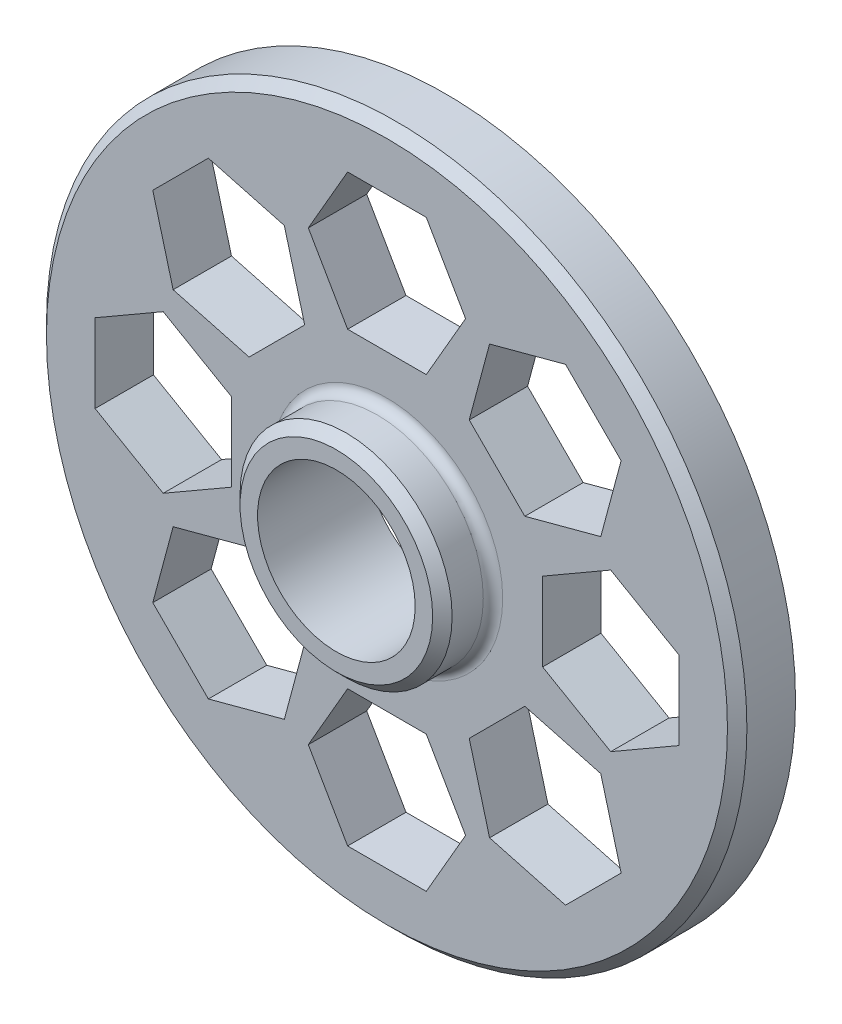
SolidWorks part; units mm, degrees
ref_plane "Alzado" through (0, 0, 0) normal (1, 0, 0) x (0, 1, 0)
ref_plane "Planta" through (0, 0, 0) normal (0, 0, 1) x (0, 1, 0)
ref_plane "Vista lateral" through (0, 0, 0) normal (0, 1, 0) x (-1, 0, 0)
sketch "Croquis1" plane through (0, 0, 0) normal (0, 0, 1) x (0, 1, 0)
  circle A0 centre (0, 0) radius 18
  dimension "D1" = 36
extrude "Saliente-Extruir1" add sketch "Croquis1" along normal blind 3
sketch "Croquis2" plane through (0, 0, 3) normal (0, 0, 1) x (1, 0, 0)
  circle A0 centre (0, 0) radius 5.45
  dimension "D1" = 10.9
extrude "Saliente-Extruir2" add sketch "Croquis2" along normal blind 2.6
chamfer "Chaflán1" distance 0.5 angle 45 2 edges at (18, 0, 3) (5.45, 0, 5.6)
fillet "Redondeo1" radius 0.5 1 edges at (5.45, 0, 3)
sketch "Croquis3" plane through (0, 0, 3) normal (0, 0, 1) x (1, 0, 0)
  line L0 (0, 0) -> (0, 18) construction
  line L2 (-4.0415, 11.5) -> (-2.0207, 8)
  line L3 (-2.0207, 8) -> (2.0207, 8)
  line L4 (2.0207, 8) -> (4.0415, 11.5)
  line L5 (4.0415, 11.5) -> (2.0207, 15)
  line L6 (2.0207, 15) -> (-2.0207, 15)
  line L7 (-2.0207, 15) -> (-4.0415, 11.5)
  circle A1 centre (0, 0) radius 18 construction
  circle A2 centre (0, 11.5) radius 3.5 construction
  dimension "D1" = 8
  dimension "D2" = 7
extrude "Cortar-Extruir1" cut sketch "Croquis3" against normal blind 3 contours L5 L6 L7 L2 L3 L4
pattern_circular "MatrizC1" count 8 over 360 about axis through (0, 0, 0) along (0, 0, 1) of "Cortar-Extruir1"
sketch "Croquis4" plane through (0, 0, 5.6) normal (0, 0, 1) x (1, 0, 0)
  circle A0 centre (0, 0) radius 4.05
  dimension "D1" = 8.1
extrude "Cortar-Extruir2" cut sketch "Croquis4" against normal through all
